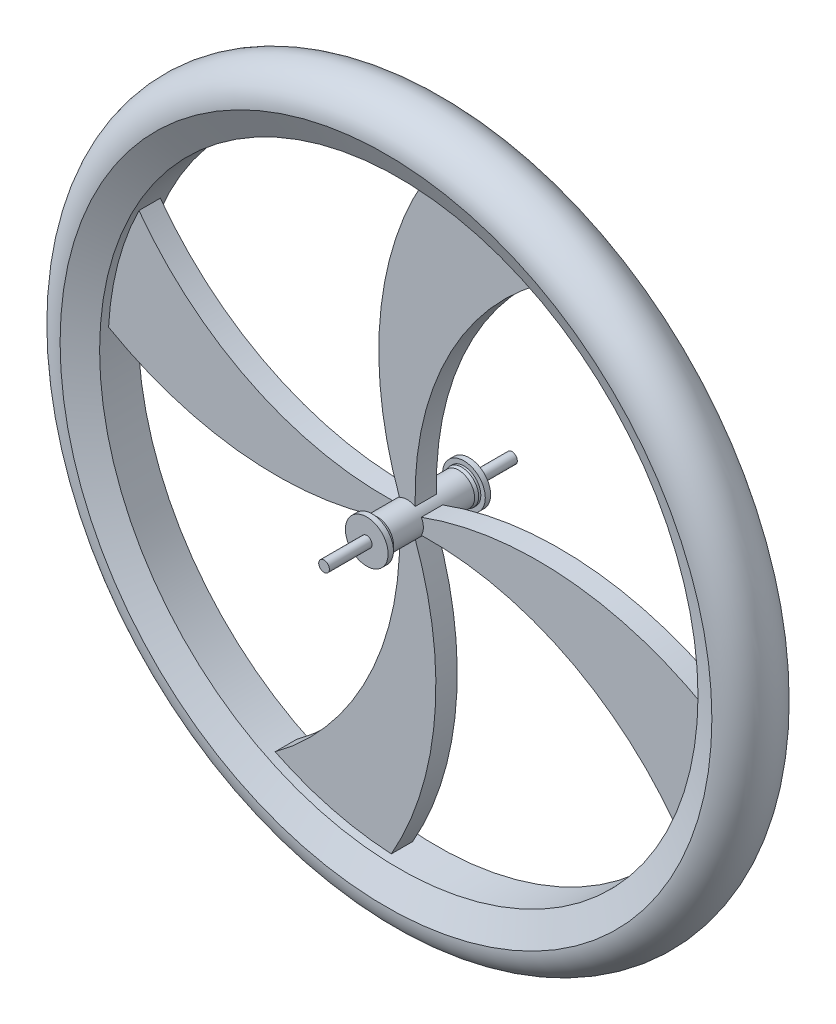
SolidWorks part; units mm, degrees
ref_plane "Front Plane" through (0, 0, 0) normal (0, 0, 1) x (1, 0, 0)
ref_plane "Top Plane" through (0, 0, 0) normal (0, 1, 0) x (1, 0, 0)
ref_plane "Right Plane" through (0, 0, 0) normal (1, 0, 0) x (0, 0, -1)
sketch "Sketch1" plane through (0, 0, 0) normal (0, 0, 1) x (1, 0, 0)
  circle A0 centre (0, 0) radius 15
extrude "Boss-Extrude1" add sketch "Sketch1" along normal blind 38
sketch "Sketch2" plane through (0, 0, 38) normal (0, 0, 1) x (1, 0, 0)
  circle A0 centre (0, 0) radius 15 construction
  circle A1 centre (0, 0) radius 15
extrude "Boss-Extrude2" add sketch "Sketch2" along normal blind 3 draft 15 draft outward yes
sketch "Sketch3" plane through (0, 0, 41) normal (0, 0, 1) x (1, 0, 0)
  circle A0 centre (0, 0) radius 15.8038 construction
  circle A1 centre (0, 0) radius 15.8038
extrude "Boss-Extrude3" add sketch "Sketch3" along normal blind 2
sketch "Sketch4" plane through (0, 0, 43) normal (0, 0, 1) x (1, 0, 0)
  circle A0 centre (0, 0) radius 20
extrude "Boss-Extrude4" add sketch "Sketch4" along normal blind 5
sketch "Sketch5" plane through (0, 0, 48) normal (0, 0, 1) x (1, 0, 0)
  circle A0 centre (0, 0) radius 5
extrude "Boss-Extrude5" add sketch "Sketch5" along normal blind 40
mirror "Mirror1" about plane through (0, 0, 0) normal (0, 0, 1) of bodies 105
ref_axis "Axis1" through (0, 0, 38) along (0, 0, -1)
sketch "Sketch6" plane through (0, 0, 0) normal (1, 0, 0) x (0, 0, -1)
  line L0 (0, 0) -> (0, 330.2) construction
  line L1 (0, 330.2) -> (30, 330.2) construction
  line L2 (30, 330.2) -> (30, 305.2) construction
  line L3 (30, 305.2) -> (0, 305.2) construction
  line L4 (-30, 305.2) -> (30, 305.2)
  line L5 (0, 305.2) -> (0, 280.2) construction
  line L6 (0, 280.2) -> (18, 280.2) construction
  line L7 (-18, 280.2) -> (18, 280.2)
  line L8 (18, 280.2) -> (30, 305.2)
  line L9 (0, 22) -> (0, -22) construction
  line L10 (-18, 280.2) -> (-30, 305.2)
revolve "Revolve1" add sketch "Sketch6" angle 360 about axis through (0, 0, 38) along (0, 0, -1)
sketch "Sketch7" plane through (0, 0, 0) normal (0, 0, 1) x (1, 0, 0)
  circle A0 centre (0, 0) radius 15 construction
  arc A1 (-7.3204, 13.0924) -> (15, 279.7982) centre (290.8994, 122.4215) cw
  circle A2 centre (0, 0) radius 280.2 construction
  arc A3 (7.3204, 13.0924) -> (123.8086, 251.3632) centre (293.4378, 20.8229) cw
  arc A4 (123.8086, 251.3632) -> (15, 279.7982) centre (0, 0) ccw
  arc A5 (-7.3204, 13.0924) -> (7.3204, 13.0924) centre (0, 0) cw
  arc A6 (13.0924, 7.3204) -> (279.7982, -15) centre (122.4215, -290.8994) cw
  arc A7 (251.3632, -123.8086) -> (279.7982, -15) centre (0, 0) ccw
  arc A8 (13.0924, -7.3204) -> (251.3632, -123.8086) centre (20.8229, -293.4378) cw
  arc A9 (13.0924, 7.3204) -> (13.0924, -7.3204) centre (0, 0) cw
  arc A10 (7.3204, -13.0924) -> (-15, -279.7982) centre (-290.8994, -122.4215) cw
  arc A11 (-123.8086, -251.3632) -> (-15, -279.7982) centre (0, 0) ccw
  arc A12 (-7.3204, -13.0924) -> (-123.8086, -251.3632) centre (-293.4378, -20.8229) cw
  arc A13 (7.3204, -13.0924) -> (-7.3204, -13.0924) centre (0, 0) cw
  arc A14 (-13.0924, -7.3204) -> (-279.7982, 15) centre (-122.4215, 290.8994) cw
  arc A15 (-251.3632, 123.8086) -> (-279.7982, 15) centre (0, 0) ccw
  arc A16 (-13.0924, 7.3204) -> (-251.3632, 123.8086) centre (-20.8229, 293.4378) cw
  arc A17 (-13.0924, -7.3204) -> (-13.0924, 7.3204) centre (0, 0) cw
  point P3 (-10.6069, 10.6063)
  point P4 (-10.6069, -10.6063)
  point P5 (10.6069, -10.6063)
  point P6 (10.6069, 10.6063)
  point P38 (0, 0)
  dimension "D1" = 4
extrude "Boss-Extrude14" add sketch "Sketch7" along normal mid plane 20
sketch "Sketch8" plane through (0, 0, 0) normal (0, 1, 0) x (1, 0, 0)
  line L0 (305.2, 30) -> (305.2, -30)
  arc A0 (305.2, 30) -> (305.2, -30) centre (305.2, 0) cw
revolve "Revolve2" add sketch "Sketch8" angle 360 about axis through (0, 0, 38) along (0, 0, -1)
